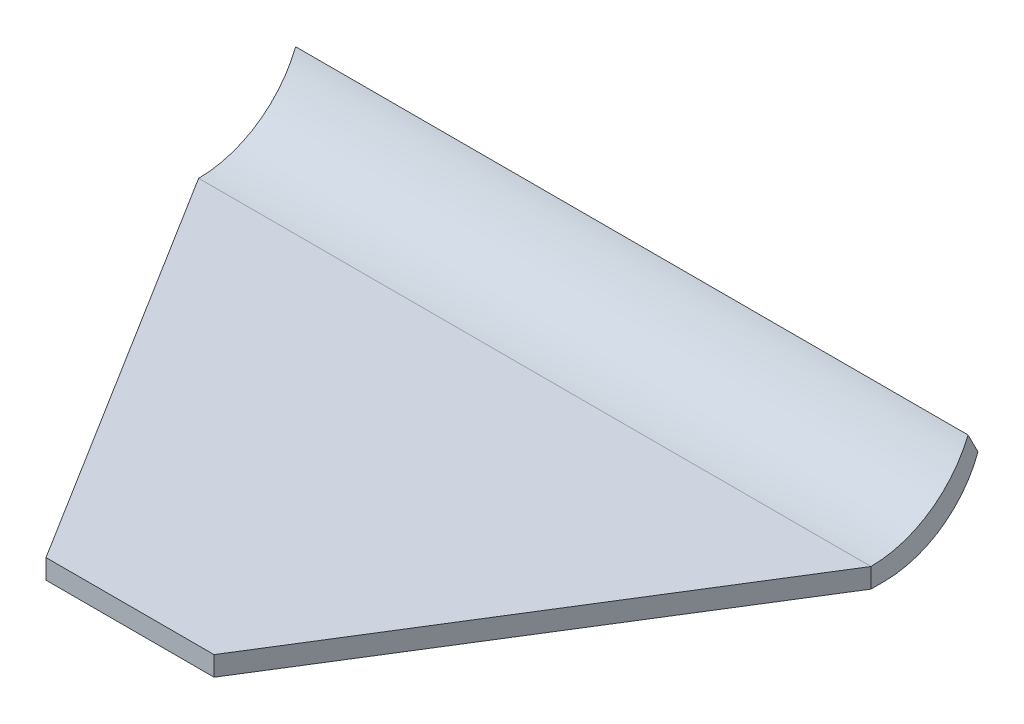
SolidWorks part; units mm, degrees
ref_plane "Front Plane" through (0, 0, 0) normal (0, 0, 1) x (1, 0, 0)
ref_plane "Top Plane" through (0, 0, 0) normal (0, 1, 0) x (1, 0, 0)
ref_plane "Right Plane" through (0, 0, 0) normal (1, 0, 0) x (0, 0, -1)
sketch "Sketch4" plane through (0, 0, 0) normal (1, 0, 0) x (0, 0, -1)
  line L0 (-167.2875, -116.7287) -> (-418.0857, -116.7287)
  line L1 (-35.25, -81.7287) -> (4.7533, -81.7287)
  line L3 (-418.0857, -81.7287) -> (-191.0156, -81.7287)
  line L4 (0, 0) -> (-17.8, 35)
  line L5 (-418.0857, -116.7287) -> (-913.4554, -116.7287)
  line L6 (-418.0857, -81.7287) -> (-913.4554, -81.7287)
  line L7 (-913.4554, -116.7287) -> (-913.4554, -81.7287)
  arc A2 (-17.8, 35) -> (-191.0156, -81.7287) centre (-191.0156, 105.1543) cw
  arc A3 (0, 0) -> (-167.2875, -116.7287) centre (-167.2875, 61.508) cw
  dimension "D3" = 35
  dimension "D4" = 35
extrude "Boss-Extrude2" add sketch "Sketch4" along normal blind 1200
sketch "Sketch5" plane through (0, -81.7287, 0) normal (0, 1, 0) x (1, 0, 0)
  line L0 (450, -913.4554) -> (750, -913.4554)
  line L1 (1200, -913.4554) -> (0, -913.4554) construction
  line L3 (450, -913.4554) -> (0, -191.0156)
  line L5 (1200, -191.0156) -> (750, -913.4554)
  line L6 (450, -913.4554) -> (0, -913.4554)
  line L7 (0, -913.4554) -> (0, -191.0156)
  line L8 (750, -913.4554) -> (1200, -913.4554)
  line L9 (1200, -913.4554) -> (1200, -191.0156)
  line M5 (0, -191.0156) -> (0, -913.4554)
  line M6 (0, -913.4554) -> (1200, -913.4554)
  line M7 (1200, -913.4554) -> (1200, -191.0156)
  dimension "D1" = 450
  dimension "D2" = 300
extrude "Cut-Extrude2" cut sketch "Sketch5" against normal blind 1200 contours L3 M6 M5 | L5 M7 M6
